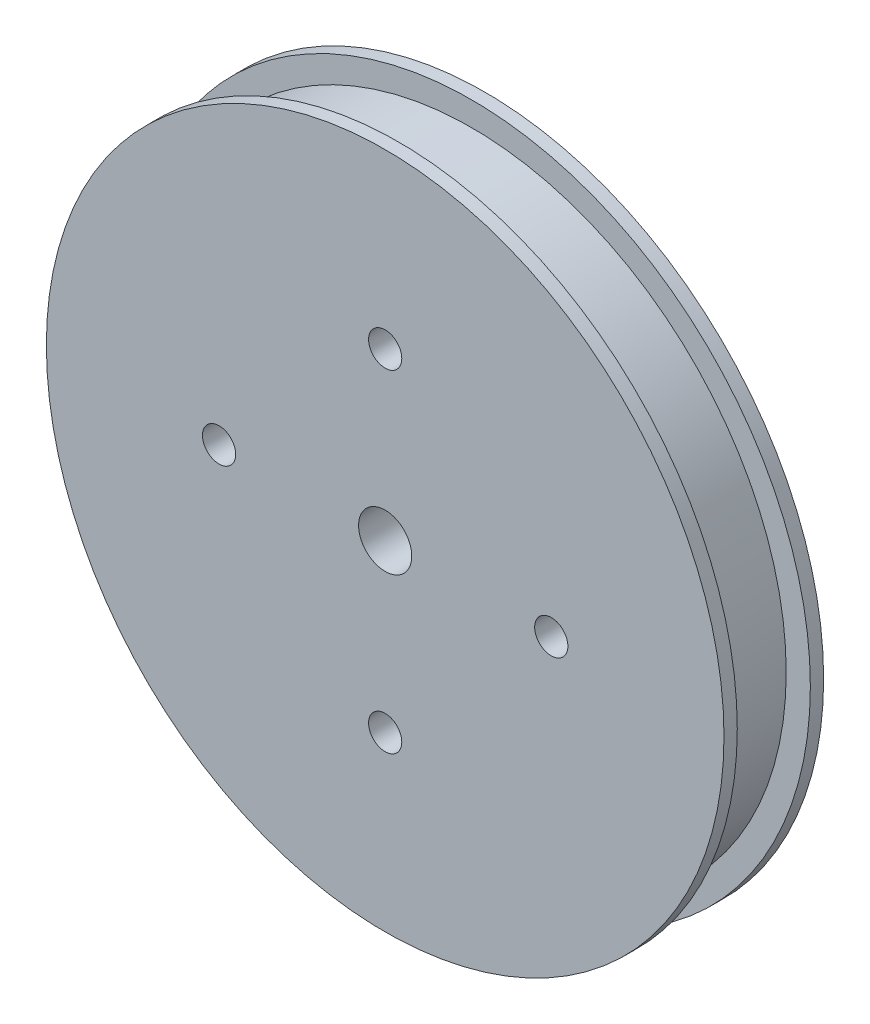
SolidWorks part; units mm, degrees
material "A1050P-H24"
ref_plane "Front" through (0, 0, 0) normal (0, 0, 1) x (1, 0, 0)
ref_plane "Top" through (0, 0, 0) normal (0, 1, 0) x (1, 0, 0)
ref_plane "Right" through (0, 0, 0) normal (1, 0, 0) x (0, 0, -1)
sketch "草图1" plane through (0, 0, 0) normal (0, 0, 1) x (1, 0, 0)
  circle A0 centre (0, 0) radius 51
  circle A1 centre (0, 0) radius 4
  dimension "D1" = 102
  dimension "D2" = 8
extrude "凸台-拉伸1" add sketch "草图1" along normal blind 15
hole_wizard "Ø5.0 (5) 直径孔1" positions "草图2" profile "草图3" hole size "Ø5.0" standard "GB" end condition up to next
sketch "草图2" plane through (0, 0, 15) normal (0, 0, 1) x (1, 0, 0)
  circle A0 centre (0, 0) radius 25
  point P5 (0, 25)
  point P7 (-25, 0)
  point P9 (0, -25)
  point P11 (25, 0)
  dimension "D1" = 50
sketch "草图3" plane through (25, 0, 15) normal (1, 0, 0) x (0, -1, 0)
  line L0 (0, 0) -> (0, 15)
  line L1 (0, 15) -> (2.5, 15)
  line L2 (2.5, 15) -> (2.5, 0)
  line L5 (2.5, 0) -> (0, 0)
  line L11 (0, -6.35) -> (0, 107.95) construction
  dimension "通孔孔直径" = 5
  dimension "通孔孔深度" = 15
sketch "草图4" plane through (0, 0, 15) normal (0, 0, 1) x (1, 0, 0)
  circle A0 centre (0, 0) radius 47.365
  circle A1 centre (0, 0) radius 51
  dimension "D1" = 94.73
extrude "切除-拉伸2" cut sketch "草图4" against normal blind 11 from offset 2
